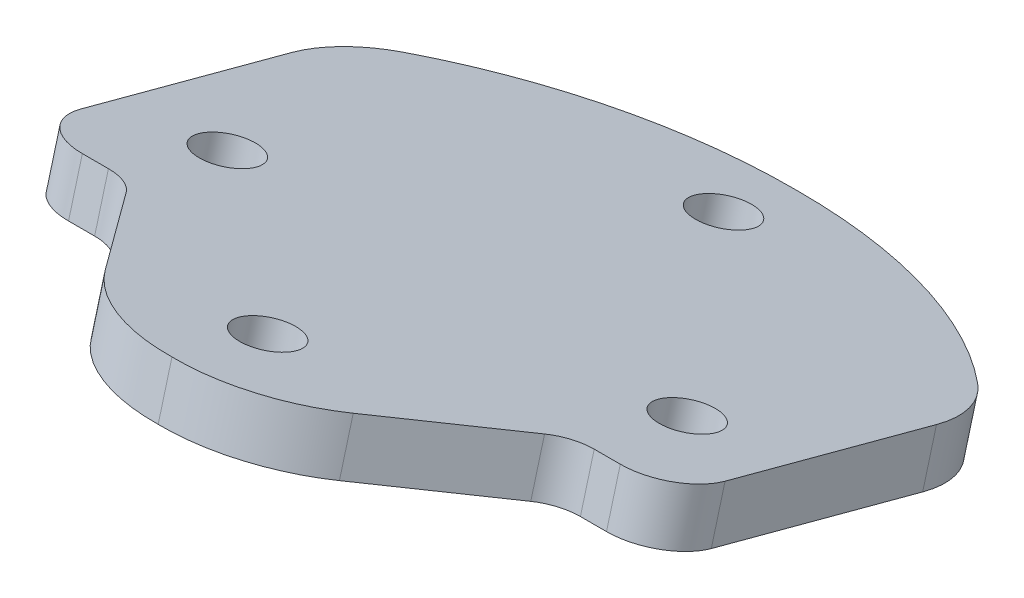
SolidWorks part; units mm, degrees
ref_plane "Front Plane" through (0, 0, 0) normal (0, 0, 1) x (1, 0, 0)
ref_plane "Top Plane" through (0, 0, 0) normal (0, 1, 0) x (1, 0, 0)
ref_plane "Right Plane" through (0, 0, 0) normal (1, 0, 0) x (0, 0, -1)
sketch "Sketch1" plane through (0, 8.8326, -2.3667) normal (0, 0.9659, -0.2588) x (1, 0, 0)
  line L0 (6.233, -16.4634) -> (6.233, -29.5014) construction
  line L1 (6.233, -16.4634) -> (6.233, -29.5014)
  line L2 (1.5038, -32.6764) -> (3.058, -32.6764) construction
  line L3 (1.5038, -32.6764) -> (3.058, -32.6764)
  line L4 (-0.5037, -33.6603) -> (-5.5782, -40.2069) construction
  line L5 (-0.5037, -33.6603) -> (-5.5782, -40.2069)
  line L6 (-25.4278, -33.6603) -> (-20.3533, -40.2069) construction
  line L7 (-25.4278, -33.6603) -> (-20.3533, -40.2069)
  line L8 (-28.9895, -32.6764) -> (-27.4353, -32.6764) construction
  line L9 (-28.9895, -32.6764) -> (-27.4353, -32.6764)
  line L10 (-32.1645, -16.4634) -> (-32.1645, -29.5014) construction
  line L11 (-32.1645, -16.4634) -> (-32.1645, -29.5014)
  arc A0 (3.058, -32.6764) -> (6.233, -29.5014) centre (3.058, -29.5014) ccw construction
  arc A1 (3.058, -32.6764) -> (6.233, -29.5014) centre (3.058, -29.5014) ccw
  arc A2 (1.5038, -32.6764) -> (-0.5037, -33.6603) centre (1.5038, -35.2164) ccw construction
  arc A3 (1.5038, -32.6764) -> (-0.5037, -33.6603) centre (1.5038, -35.2164) ccw
  arc A4 (-12.9658, -43.7382) -> (-5.5782, -40.2069) centre (-12.7869, -34.6192) ccw construction
  arc A5 (-12.9658, -43.7382) -> (-5.5782, -40.2069) centre (-12.7869, -34.6192) ccw
  arc A6 (-20.3533, -40.2069) -> (-12.9658, -43.7382) centre (-13.1446, -34.6192) ccw construction
  arc A7 (-20.3533, -40.2069) -> (-12.9658, -43.7382) centre (-13.1446, -34.6192) ccw
  arc A8 (-25.4278, -33.6603) -> (-27.4353, -32.6764) centre (-27.4353, -35.2164) ccw construction
  arc A9 (-25.4278, -33.6603) -> (-27.4353, -32.6764) centre (-27.4353, -35.2164) ccw
  arc A10 (-32.1645, -29.5014) -> (-28.9895, -32.6764) centre (-28.9895, -29.5014) ccw construction
  arc A11 (-32.1645, -29.5014) -> (-28.9895, -32.6764) centre (-28.9895, -29.5014) ccw
  arc A12 (-30.0564, -11.7381) -> (-32.1645, -16.4634) centre (-25.8145, -16.4634) ccw construction
  arc A13 (-30.0564, -11.7381) -> (-32.1645, -16.4634) centre (-25.8145, -16.4634) ccw
  arc A14 (-12.9658, -5.2613) -> (-30.0564, -11.7381) centre (-13.1446, -30.5768) ccw construction
  arc A15 (-12.9658, -5.2613) -> (-30.0564, -11.7381) centre (-13.1446, -30.5768) ccw
  arc A16 (4.1249, -11.7381) -> (-12.9658, -5.2613) centre (-12.7869, -30.5768) ccw construction
  arc A17 (4.1249, -11.7381) -> (-12.9658, -5.2613) centre (-12.7869, -30.5768) ccw
  arc A18 (6.233, -16.4634) -> (4.1249, -11.7381) centre (-0.117, -16.4634) ccw construction
  arc A19 (6.233, -16.4634) -> (4.1249, -11.7381) centre (-0.117, -16.4634) ccw
  circle A20 centre (0.9167, -26.3327) radius 1.7272 construction
  circle A21 centre (0.9167, -26.3327) radius 1.7272
  circle A22 centre (-12.7823, -38.0257) radius 1.7272 construction
  circle A23 centre (-12.7823, -38.0257) radius 1.7272
  circle A24 centre (-26.4814, -26.3327) radius 1.7272 construction
  circle A25 centre (-26.4814, -26.3327) radius 1.7272
  circle A26 centre (-12.7823, -9.9114) radius 1.7272 construction
  circle A27 centre (-12.7823, -9.9114) radius 1.7272
extrude "Extrude1" add sketch "Sketch1" along normal blind 3.175
